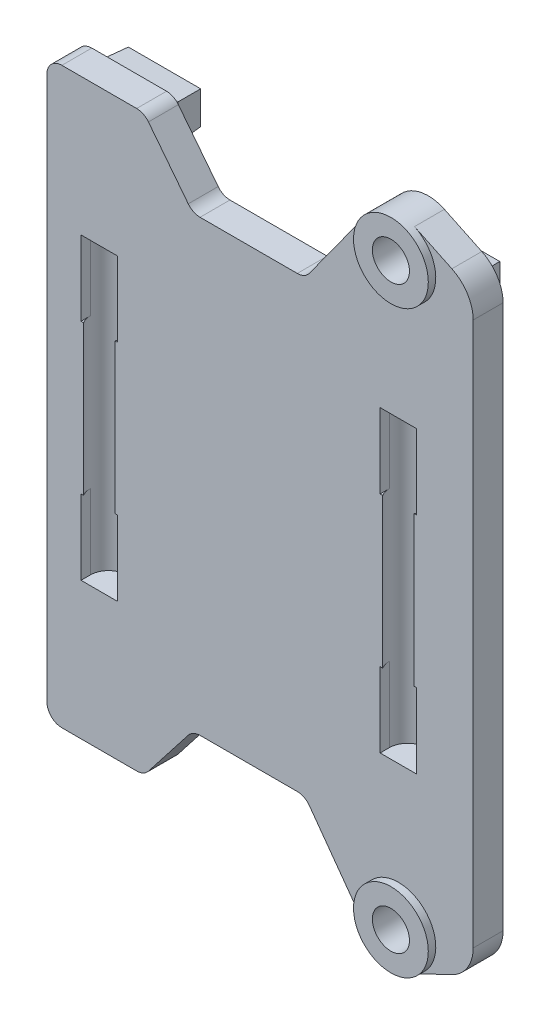
SolidWorks part; units mm, degrees
ref_plane "Front Plane" through (0, 0, 0) normal (0, 0, 1) x (1, 0, 0)
ref_plane "Top Plane" through (0, 0, 0) normal (0, 1, 0) x (1, 0, 0)
ref_plane "Right Plane" through (0, 0, 0) normal (1, 0, 0) x (0, 0, -1)
sketch "Sketch1" plane through (0, 0, 0) normal (0, 0, 1) x (1, 0, 0)
  line L0 (0, 0) -> (190.5, 0) construction
  line L1 (190.5, 28.575) -> (190.5, -28.575) construction
  line L2 (-190.5, -22.225) -> (-190.5, 34.925) construction
  line L3 (190.5, -19.05) -> (-190.5, -19.05) construction
  line L4 (190.5, -19.05) -> (190.5, 19.05) construction
  line L5 (190.5, 19.05) -> (-190.5, 19.05) construction
  line L6 (-190.5, -19.05) -> (-190.5, 19.05) construction
  line L7 (190.5, -19.05) -> (-190.5, 19.05) construction
  line L8 (190.5, 19.05) -> (-190.5, -19.05) construction
  dimension "D1" = 38.1
sketch "Sketch2" plane through (0, 0, 0) normal (0, 0, 1) x (1, 0, 0)
  line L0 (190.5, 19.05) -> (-190.5, 19.05) construction
  line L1 (161.925, 23.09) -> (187.325, 23.09) construction
  line L2 (185.5182, 27.4713) -> (188.6932, 25.9551)
  line L3 (190.5, 23.09) -> (190.5, 0)
  line L4 (190.5, 0) -> (154.305, 0)
  line L5 (0, 0) -> (190.5, 0) construction
  line L6 (154.305, 0) -> (154.305, 23.09)
  line L7 (155.575, 24.36) -> (161.925, 24.36)
  line L8 (162.9263, 23.8712) -> (166.3062, 19.5388)
  line L9 (167.3075, 19.05) -> (175.5637, 19.05)
  line L10 (176.5927, 19.5757) -> (181.5774, 26.467)
  line L13 (161.925, 23.09) -> (155.575, 23.09) construction
  line L14 (161.925, 23.09) -> (161.925, 20.09) construction
  line L15 (161.925, 20.09) -> (155.575, 20.09) construction
  line L16 (155.575, 23.09) -> (155.575, 20.09) construction
  line L17 (161.925, 23.09) -> (155.575, 20.09) construction
  line L18 (161.925, 20.09) -> (155.575, 23.09) construction
  circle A0 centre (184.15, 24.6063) radius 5.5563 construction
  circle A1 centre (184.15, 24.6063) radius 1.575
  circle A2 centre (184.15, 24.6063) radius 4.5 construction
  arc A4 (185.5182, 27.4713) -> (181.5774, 26.467) centre (184.15, 24.6063) ccw
  arc A5 (188.6932, 25.9551) -> (190.5, 23.09) centre (187.325, 23.09) cw
  arc A8 (176.5927, 19.5757) -> (175.5637, 19.05) centre (175.5637, 20.32) cw
  arc A9 (167.3075, 19.05) -> (166.3062, 19.5388) centre (167.3075, 20.32) cw
  arc A10 (162.9263, 23.8712) -> (161.925, 24.36) centre (161.925, 23.09) ccw
  arc A11 (155.575, 24.36) -> (154.305, 23.09) centre (155.575, 23.09) ccw
  point P27 (158.75, 21.59)
  point P32 (176.2125, 19.05)
  point P36 (166.6875, 19.05)
  dimension "D1" = 3.15
  dimension "D2" = 11.1125
  dimension "D3" = 9
  dimension "D5" = 6.35
  dimension "D8" = 1.27
  dimension "D4" = 6.35
  dimension "D6" = 14.2875
  dimension "D7" = 9.525
  dimension "D9" = 31.75
  dimension "D10" = 6.35
  dimension "D11" = 3
  dimension "D12" = 2.54
extrude "Boss-Extrude1" add sketch "Sketch2" along normal blind 2.54 contours L7 A11 L6 L4 L3 A5 L2 A4 L10 A8 L9 A9 L8 A10
sketch "Sketch3" plane through (0, 0, 2.54) normal (0, 0, 1) x (1, 0, 0)
  circle A0 centre (184.15, 24.6063) radius 1.575
  circle A1 centre (184.15, 24.6063) radius 3.175
  circle A2 centre (184.15, 24.6063) radius 1.575 construction
extrude "Boss-Extrude2" add sketch "Sketch3" along normal offset from surface (0.635 mm away) 3.175 up to face at (185.725, 24.6063, 0)
sketch "Sketch4" plane through (0, 0, 0) normal (0, 0, -1) x (-1, 0, 0)
  line L0 (0, 0) -> (-190.5, 0) construction
  line L1 (-187.325, 23.09) -> (-180.975, 23.09)
  line L2 (-187.325, 23.09) -> (-187.325, 20.09)
  line L3 (-187.325, 20.09) -> (-180.975, 20.09)
  line L4 (-180.975, 23.09) -> (-180.975, 20.09)
  line L5 (-187.325, 23.09) -> (-180.975, 20.09) construction
  line L6 (-187.325, 20.09) -> (-180.975, 23.09) construction
  line L7 (-161.925, 23.09) -> (-155.575, 23.09)
  line L8 (-161.925, 23.09) -> (-161.925, 20.09)
  line L9 (-161.925, 20.09) -> (-155.575, 20.09)
  line L10 (-155.575, 23.09) -> (-155.575, 20.09)
  line L11 (-161.925, 23.09) -> (-155.575, 20.09) construction
  line L12 (-161.925, 20.09) -> (-155.575, 23.09) construction
  line L13 (-190.5, -19.05) -> (-190.5, 19.05) construction
  point P0 (-184.15, 21.59)
  point P5 (-158.75, 21.59)
  dimension "D1" = 21.59
  dimension "D2" = 6.35
  dimension "D3" = 3
  dimension "D4" = 6.35
  dimension "D5" = 25.4
extrude "Boss-Extrude3" add sketch "Sketch4" along normal blind 1
sketch "Sketch5" plane through (0, 0, -1) normal (0, 0, -1) x (-1, 0, 0)
  line L0 (-155.575, 20.09) -> (-155.575, 23.09) construction
  line L1 (-155.575, 23.09) -> (-161.925, 23.09) construction
  line L2 (-161.925, 23.09) -> (-161.925, 20.09) construction
  line L3 (-161.925, 20.09) -> (-155.575, 20.09) construction
  line L4 (-180.975, 20.09) -> (-180.975, 23.09) construction
  line L5 (-180.975, 23.09) -> (-187.325, 23.09) construction
  line L6 (-187.325, 23.09) -> (-187.325, 20.09) construction
  line L7 (-187.325, 20.09) -> (-180.975, 20.09) construction
  line L8 (-155.575, 20.09) -> (-155.575, 23.09)
  line L9 (-155.575, 23.09) -> (-161.925, 23.09)
  line L10 (-161.925, 23.09) -> (-161.925, 20.09)
  line L11 (-161.925, 20.09) -> (-155.575, 20.09)
  line L12 (-180.975, 20.09) -> (-180.975, 23.09)
  line L13 (-180.975, 23.09) -> (-187.325, 23.09)
  line L14 (-187.325, 23.09) -> (-187.325, 20.09)
  line L15 (-187.325, 20.09) -> (-180.975, 20.09)
extrude "Boss-Extrude4" add sketch "Sketch5" along normal offset from surface 3 draft 3
sketch "Sketch6" plane through (0, 0, 0) normal (0, -1, 0) x (1, 0, 0)
  line L1 (190.5, 2.54) -> (190.5, 0) construction
  line L2 (190.5, 0) -> (154.305, 0) construction
  circle A0 centre (184.15, 1.752) radius 1.55
  point P5 (184.15, 3.302)
  dimension "D3" = 3.1
  dimension "D4" = 3.302
  dimension "D2" = 6.35
extrude "Cut-Extrude1" cut sketch "Sketch6" against normal blind 12.7
sketch "Sketch7" plane through (0, 0, 2.54) normal (0, 0, 1) x (1, 0, 0)
  line L1 (185.7, 6.35) -> (182.6, 6.35)
  line L2 (185.7, 6.35) -> (185.7, 12.7)
  line L3 (185.7, 12.7) -> (182.6, 12.7) construction
  line L4 (182.6, 6.35) -> (182.6, 12.7)
  line L5 (185.7, 6.35) -> (182.6, 12.7) construction
  line L6 (185.7, 12.7) -> (182.6, 6.35) construction
  line L13 (182.6, 12.7) -> (185.7, 12.7) construction
  line L14 (182.6, 12.7) -> (185.7, 12.7)
  point P0 (184.15, 9.525)
  dimension "D1" = 6.35
extrude "Cut-Extrude2" cut sketch "Sketch7" against normal up to next
sketch "Sketch8" plane through (0, 0, 2.54) normal (0, 0, 1) x (1, 0, 0)
  line L0 (0, 0) -> (190.5, 0) construction
  line L1 (183.515, 0) -> (184.785, 0)
  line L2 (183.515, 0) -> (183.515, 6.35)
  line L3 (183.515, 6.35) -> (184.785, 6.35)
  line L4 (184.785, 0) -> (184.785, 6.35)
  line L5 (183.515, 0) -> (184.785, 6.35) construction
  line L6 (183.515, 6.35) -> (184.785, 0) construction
  line L9 (184.15, 3.175) -> (184.15, 12.7) construction
  line L10 (182.6, 12.7) -> (185.7, 12.7) construction
  point P0 (184.15, 3.175)
  point P5 (184.15, 0)
  dimension "D1" = 6.35
  dimension "D2" = 1.27
extrude "Cut-Extrude3" cut sketch "Sketch8" against normal up to next
pattern_linear "LPattern1" count 2 spacing 25.4 along (-1, 0, 0) of "Cut-Extrude1", "Cut-Extrude2", "Cut-Extrude3"
mirror "Mirror1" about plane through (0, 0, 0) normal (0, 1, 0) of bodies 109 102
